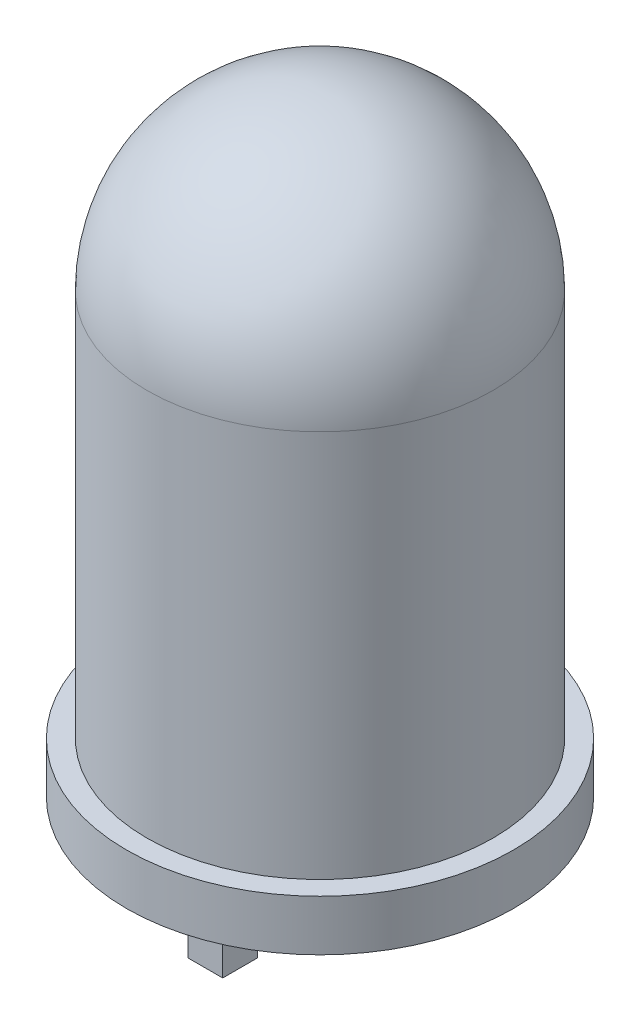
SolidWorks part; units mm, degrees
ref_plane "Front Plane" through (0, 0, 0) normal (0, 0, 1) x (1, 0, 0)
ref_plane "Top Plane" through (0, 0, 0) normal (0, 1, 0) x (1, 0, 0)
ref_plane "Right Plane" through (0, 0, 0) normal (1, 0, 0) x (0, 0, -1)
sketch "Sketch1" plane through (0, 0, 0) normal (0, 0, 1) x (1, 0, 0)
  line L0 (0, -4.4) -> (0, 4.4)
  line L1 (2.49, 1.91) -> (2.49, -3.6699)
  line L2 (2.49, -3.6699) -> (2.785, -3.6699)
  line L3 (2.785, -3.6699) -> (2.785, -4.4)
  line L4 (2.785, -4.4) -> (0, -4.4)
  arc A0 (0, 4.4) -> (2.49, 1.91) centre (0, 1.91) cw
  dimension "D1" = 8.8
  dimension "D2" = 2.49
  dimension "D3" = 2.785
revolve "Revolve1" add sketch "Sketch1" angle 360 about L0
sketch "Sketch2" plane through (0, -4.4, 0) normal (0, -1, 0) x (1, 0, 0)
  line L0 (0, -1.15) -> (0, 1.15) construction
  line L1 (0.25, -1.65) -> (-0.25, -1.65)
  line L2 (0.25, -1.65) -> (0.25, -1.15)
  line L3 (0.25, -1.15) -> (-0.25, -1.15)
  line L4 (-0.25, -1.65) -> (-0.25, -1.15)
  line L5 (0.25, 1.15) -> (-0.25, 1.15)
  line L6 (0.25, 1.15) -> (0.25, 1.65)
  line L7 (0.25, 1.65) -> (-0.25, 1.65)
  line L8 (-0.25, 1.15) -> (-0.25, 1.65)
  dimension "D1" = 0.5
  dimension "D2" = 3.3
extrude "Boss-Extrude1" add sketch "Sketch2" along normal blind 2
sketch "Sketch3" plane through (0.25, 0, 0) normal (1, 0, 0) x (0, 0, -1)
  line L1 (0.2112, -8.2633) -> (-2.9138, -8.2633)
  line L2 (0.2112, -8.2633) -> (0.2112, -5.7076)
  line L3 (0.2112, -5.7076) -> (-2.9138, -5.7076)
  line L4 (-2.9138, -8.2633) -> (-2.9138, -5.7076)
extrude "Cut-Extrude1" cut sketch "Sketch3" against normal through all both and the other way through all
